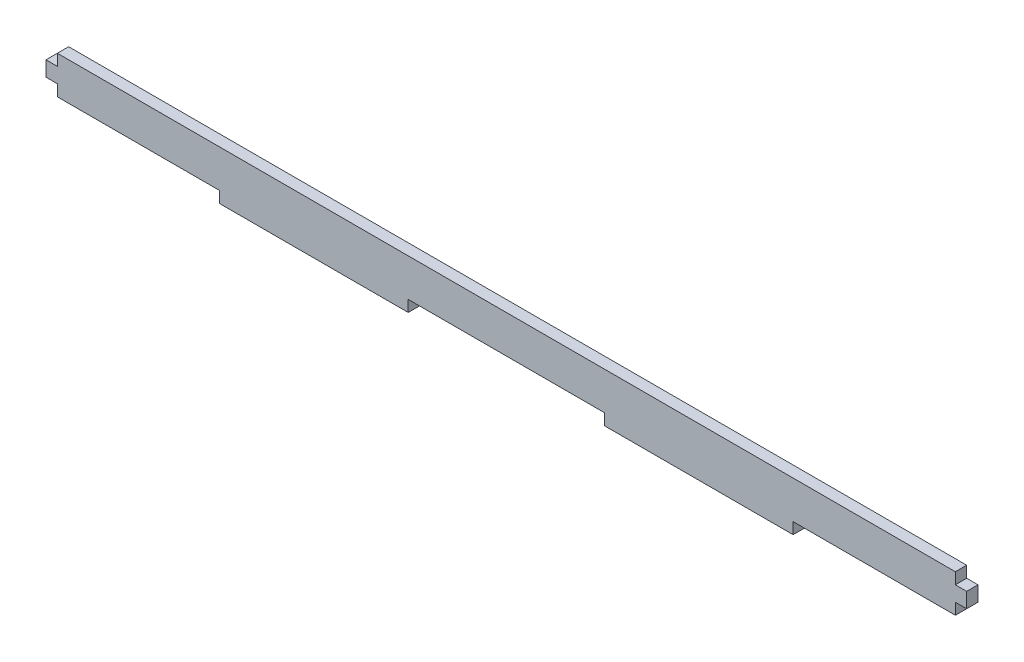
SolidWorks part; units mm, degrees
ref_plane "Front Plane" through (0, 0, 0) normal (0, 0, 1) x (1, 0, 0)
ref_plane "Top Plane" through (0, 0, 0) normal (0, 1, 0) x (1, 0, 0)
ref_plane "Right Plane" through (0, 0, 0) normal (1, 0, 0) x (0, 0, -1)
sketch "Sketch1" plane through (0, 0, 0) normal (0, 0, 1) x (1, 0, 0)
  line L0 (93, 0) -> (145, 0)
  line L1 (0, 0) -> (43, 0)
  line L2 (0, 0) -> (0, 3)
  line L3 (0, 10) -> (238, 10)
  line L4 (238, 0) -> (238, 3)
  line L5 (195, 0) -> (238, 0)
  line L6 (43, 0) -> (43, -3)
  line L7 (43, -3) -> (93, -3)
  line L8 (93, 0) -> (93, -3)
  line L9 (0, 7) -> (0, 10)
  line L10 (145, 0) -> (145, -3)
  line L11 (145, -3) -> (195, -3)
  line L12 (195, 0) -> (195, -3)
  line L13 (0, 7) -> (-3, 7)
  line L14 (238, 7) -> (238, 10)
  line L15 (0, 3) -> (-3, 3)
  line L16 (-3, 7) -> (-3, 3)
  line L17 (238, 7) -> (241, 7)
  line L19 (238, 3) -> (241, 3)
  line L20 (241, 7) -> (241, 3)
  dimension "D1" = 50
  dimension "D2" = 50
  dimension "D3" = 238
  dimension "D4" = 43
  dimension "D5" = 52
  dimension "D6" = 3
  dimension "D7" = 3
  dimension "D8" = 10
  dimension "D9" = 4
  dimension "D10" = 3
  dimension "D11" = 3
  dimension "D12" = 4
  dimension "D13" = 3
  dimension "D14" = 3
extrude "Boss-Extrude1" add sketch "Sketch1" along normal blind 3
